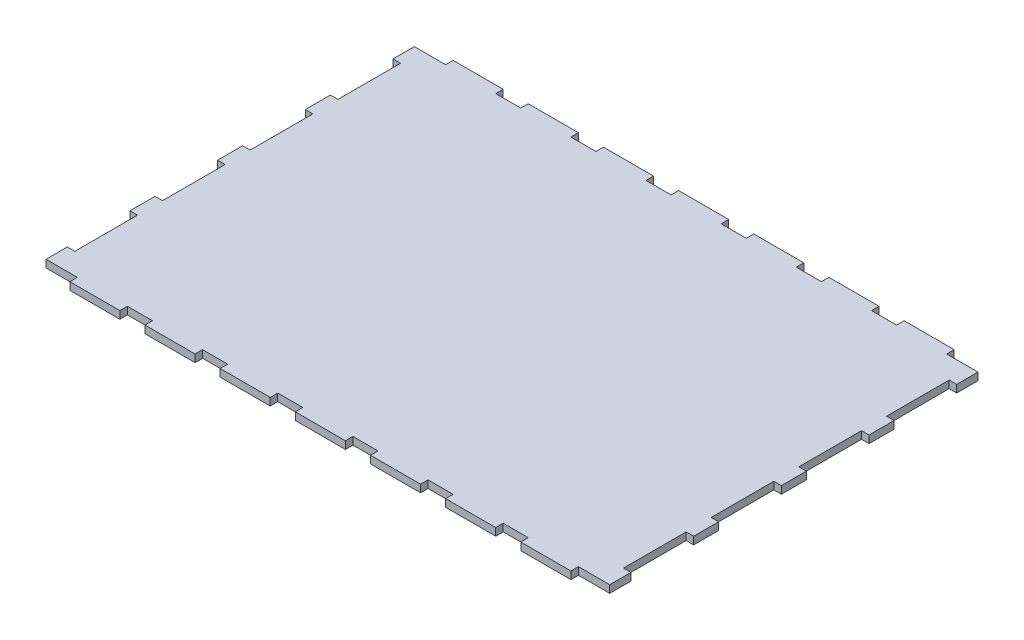
SolidWorks part; units mm, degrees
ref_plane "Plan de face" through (0, 0, 0) normal (0, 0, 1) x (1, 0, 0)
ref_plane "Plan de dessus" through (0, 0, 0) normal (0, 1, 0) x (1, 0, 0)
ref_plane "Plan de droite" through (0, 0, 0) normal (1, 0, 0) x (0, 0, -1)
sketch "Esquisse1" plane through (0, 0, 0) normal (0, 1, 0) x (1, 0, 0)
  line L1 (0, 0) -> (25, 0)
  line L2 (0, 0) -> (0, 17)
  line L3 (0, 294) -> (25, 294)
  line L6 (25, 0) -> (25, -6)
  line L7 (25, -6) -> (65, -6)
  line L8 (65, 0) -> (65, -6)
  line L9 (85, 0) -> (85, -6)
  line L10 (85, -6) -> (125, -6)
  line L11 (125, 0) -> (125, -6)
  line L13 (145, 0) -> (145, -6)
  line L14 (145, -6) -> (185, -6)
  line L15 (185, 0) -> (185, -6)
  line L17 (205, 0) -> (205, -6)
  line L18 (205, -6) -> (245, -6)
  line L19 (245, 0) -> (245, -6)
  line L21 (265, 0) -> (265, -6)
  line L22 (265, -6) -> (305, -6)
  line L23 (305, 0) -> (305, -6)
  line L25 (325, 0) -> (325, -6)
  line L26 (325, -6) -> (365, -6)
  line L27 (365, 0) -> (365, -6)
  line L29 (385, 0) -> (385, -6)
  line L30 (385, -6) -> (425, -6)
  line L31 (425, 0) -> (425, -6)
  line L32 (65, 0) -> (85, 0)
  line L33 (125, 0) -> (145, 0)
  line L34 (185, 0) -> (205, 0)
  line L35 (245, 0) -> (265, 0)
  line L36 (305, 0) -> (325, 0)
  line L37 (365, 0) -> (385, 0)
  line L38 (425, 0) -> (450, 0)
  line L39 (0, 147) -> (450, 147) construction
  line L40 (0, 207) -> (6, 207)
  line L41 (0, 277) -> (6, 277)
  line L43 (0, 227) -> (6, 227)
  line L44 (6, 277) -> (6, 227)
  line L46 (425, 294) -> (425, 300)
  line L47 (385, 300) -> (425, 300)
  line L48 (385, 294) -> (385, 300)
  line L49 (365, 294) -> (365, 300)
  line L50 (325, 300) -> (365, 300)
  line L51 (325, 294) -> (325, 300)
  line L52 (305, 294) -> (305, 300)
  line L53 (265, 300) -> (305, 300)
  line L54 (265, 294) -> (265, 300)
  line L55 (245, 294) -> (245, 300)
  line L56 (205, 300) -> (245, 300)
  line L57 (205, 294) -> (205, 300)
  line L58 (185, 294) -> (185, 300)
  line L59 (145, 300) -> (185, 300)
  line L60 (145, 294) -> (145, 300)
  line L61 (125, 294) -> (125, 300)
  line L62 (85, 300) -> (125, 300)
  line L63 (85, 294) -> (85, 300)
  line L64 (65, 294) -> (65, 300)
  line L65 (25, 300) -> (65, 300)
  line L66 (25, 294) -> (25, 300)
  line L67 (425, 294) -> (450, 294)
  line L68 (365, 294) -> (385, 294)
  line L69 (305, 294) -> (325, 294)
  line L70 (245, 294) -> (265, 294)
  line L71 (185, 294) -> (205, 294)
  line L72 (125, 294) -> (145, 294)
  line L73 (65, 294) -> (85, 294)
  line L74 (0, 157) -> (6, 157)
  line L75 (6, 207) -> (6, 157)
  line L76 (0, 137) -> (6, 137)
  line L78 (0, 87) -> (6, 87)
  line L79 (6, 137) -> (6, 87)
  line L80 (0, 67) -> (6, 67)
  line L82 (0, 17) -> (6, 17)
  line L83 (6, 67) -> (6, 17)
  line L84 (0, 67) -> (0, 87)
  line L85 (450, 17) -> (450, 0)
  line L87 (0, 137) -> (0, 157)
  line L89 (0, 207) -> (0, 227)
  line L90 (0, 277) -> (0, 294)
  line L91 (225, 300) -> (225, -6) construction
  line L95 (444, 67) -> (444, 17)
  line L96 (450, 17) -> (444, 17)
  line L97 (450, 67) -> (444, 67)
  line L98 (444, 137) -> (444, 87)
  line L99 (450, 87) -> (444, 87)
  line L100 (450, 137) -> (444, 137)
  line L101 (444, 207) -> (444, 157)
  line L102 (450, 157) -> (444, 157)
  line L103 (444, 277) -> (444, 227)
  line L104 (450, 227) -> (444, 227)
  line L105 (450, 277) -> (444, 277)
  line L106 (450, 207) -> (444, 207)
  line L107 (450, 277) -> (450, 294)
  line L108 (450, 207) -> (450, 227)
  line L109 (450, 137) -> (450, 157)
  line L110 (450, 67) -> (450, 87)
  dimension "D1" = 294
  dimension "D2" = 450
  dimension "D3" = 40
  dimension "D4" = 25
  dimension "D7" = 6
  dimension "D8" = 6
  dimension "D9" = 50
  dimension "D10" = 17
  dimension "D12" = 17
  dimension "D5" = 7
  dimension "D11" = 4
extrude "Boss.-Extru.1" add sketch "Esquisse1" along normal blind 6
